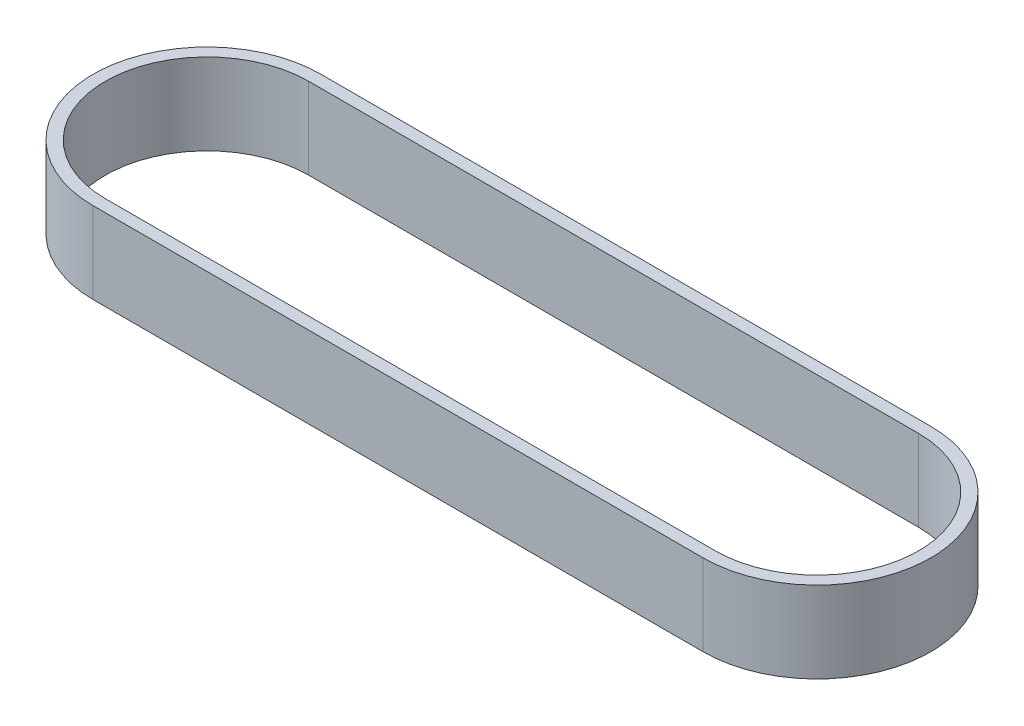
SolidWorks part; units mm, degrees
material "Silicon Rubber"
ref_plane "Front Plane" through (0, 0, 0) normal (0, 0, 1) x (1, 0, 0)
ref_plane "Top Plane" through (0, 0, 0) normal (0, 1, 0) x (1, 0, 0)
ref_plane "Right Plane" through (0, 0, 0) normal (1, 0, 0) x (0, 0, -1)
sketch "Sketch1" plane through (0, 0, 0) normal (0, 1, 0) x (1, 0, 0)
  line L0 (-150, 0) -> (150, 0) construction
  line L1 (-150, 50) -> (150, 50)
  line L2 (-150, -50) -> (150, -50)
  line L3 (-150, 56) -> (150, 56)
  line L4 (-150, -56) -> (150, -56)
  arc A0 (-150, 50) -> (-150, -50) centre (-150, 0) ccw
  arc A1 (150, -50) -> (150, 50) centre (150, 0) ccw
  arc A2 (150, -56) -> (150, 56) centre (150, 0) ccw
  arc A3 (-150, 56) -> (-150, -56) centre (-150, 0) ccw
  point P3 (0, 0)
  point P8 (0, 50)
  point P15 (0, 0)
  dimension "D2" = 50
  dimension "D1" = 300
  dimension "D4" = 300
  dimension "D3" = 6
extrude "Boss-Extrude1" add sketch "Sketch1" along normal blind 40
